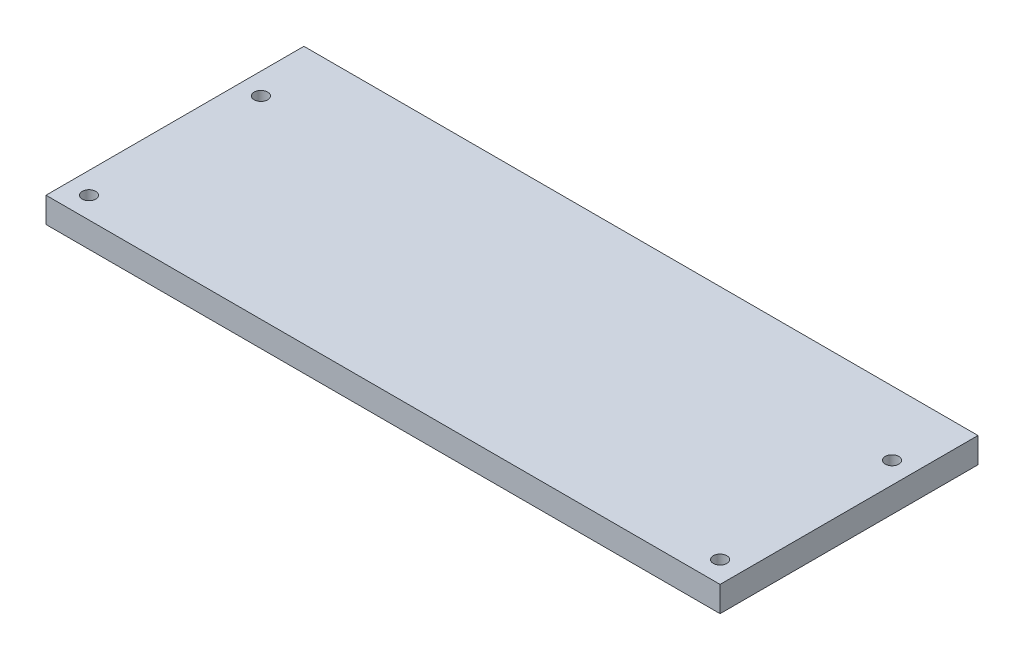
SolidWorks part; units mm, degrees
material "轻木"
ref_plane "Front" through (0, 0, 0) normal (0, 0, 1) x (1, 0, 0)
ref_plane "Top" through (0, 0, 0) normal (0, 1, 0) x (1, 0, 0)
ref_plane "Right" through (0, 0, 0) normal (1, 0, 0) x (0, 0, -1)
sketch "草图1" plane through (0, 0, 0) normal (0, 1, 0) x (1, 0, 0)
  line L0 (385.6, 71.408) -> (385.6, 139.9319) construction
  line L1 (0, 0) -> (398.3, 0)
  line L2 (0, 0) -> (0, 152.4)
  line L3 (0, 152.4) -> (398.3, 152.4)
  line L4 (398.3, 0) -> (398.3, 152.4)
  line L5 (254.7419, 12.7) -> (183.1786, 12.7) construction
  line L6 (12.7, 115.7639) -> (12.7, 163.1581) construction
  circle A0 centre (12.7, 114.3) radius 4
  circle A1 centre (12.7, 12.7) radius 4
  circle A2 centre (385.6, 114.3) radius 4
  circle A3 centre (385.6, 12.7) radius 4
  point P14 (0, 0)
  dimension "D3" = 8
  dimension "D4" = 8
  dimension "D5" = 8
  dimension "D6" = 8
  dimension "D1" = 398.3
  dimension "D2" = 152.4
  dimension "D7" = 12.7
  dimension "D8" = 12.7
  dimension "D9" = 12.7
  dimension "D10" = 101.6
  dimension "D11" = 101.6
extrude "凸台-拉伸1" add sketch "草图1" along normal blind 15
